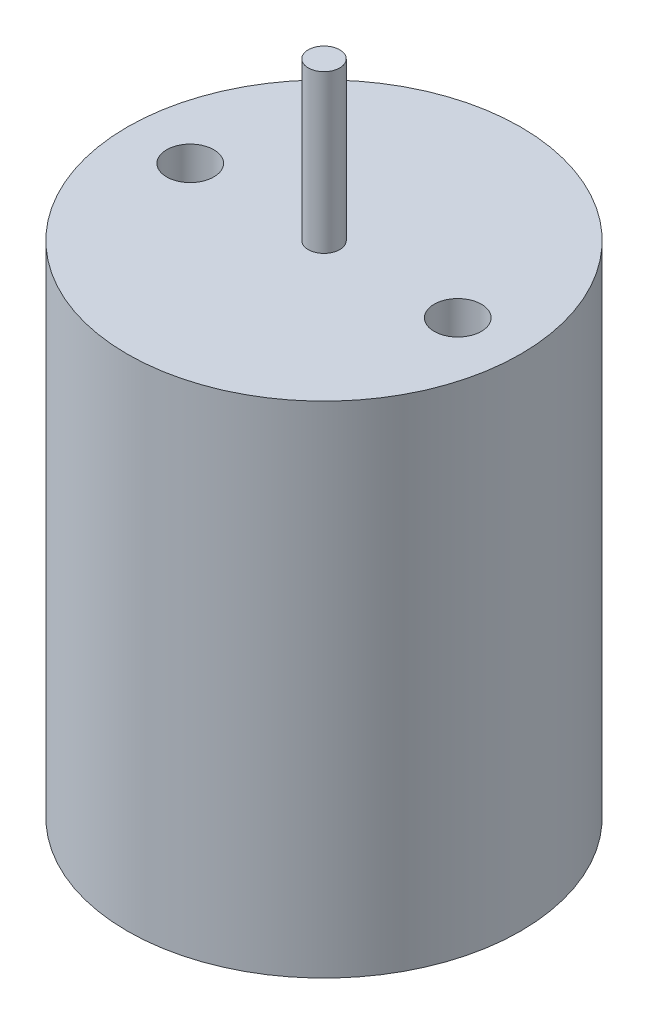
SolidWorks part; units mm, degrees
ref_plane "Front Plane" through (0, 0, 0) normal (0, 0, 1) x (1, 0, 0)
ref_plane "Top Plane" through (0, 0, 0) normal (0, 1, 0) x (1, 0, 0)
ref_plane "Right Plane" through (0, 0, 0) normal (1, 0, 0) x (0, 0, -1)
sketch "Sketch1" plane through (0, 0, 0) normal (0, 1, 0) x (1, 0, 0)
  circle A0 centre (0, 0) radius 12.5
  dimension "D1" = 25
extrude "Boss-Extrude1" add sketch "Sketch1" along normal blind 31.75
sketch "Sketch2" plane through (0, 31.75, 0) normal (0, 1, 0) x (1, 0, 0)
  circle A0 centre (0, 0) radius 1
  dimension "D1" = 2
extrude "Boss-Extrude2" add sketch "Sketch2" along normal blind 10
sketch "Sketch3" plane through (0, 31.75, 0) normal (0, 1, 0) x (1, 0, 0)
  line L0 (-8.5, 0) -> (8.5, 0) construction
  circle A0 centre (-8.5, 0) radius 1.5
  circle A1 centre (8.5, 0) radius 1.5
  point P3 (0, 0)
  dimension "D3" = 3
  dimension "D4" = 3
  dimension "D1" = 17
  dimension "D2" = 0
extrude "Cut-Extrude1" cut sketch "Sketch3" against normal blind 6.35
